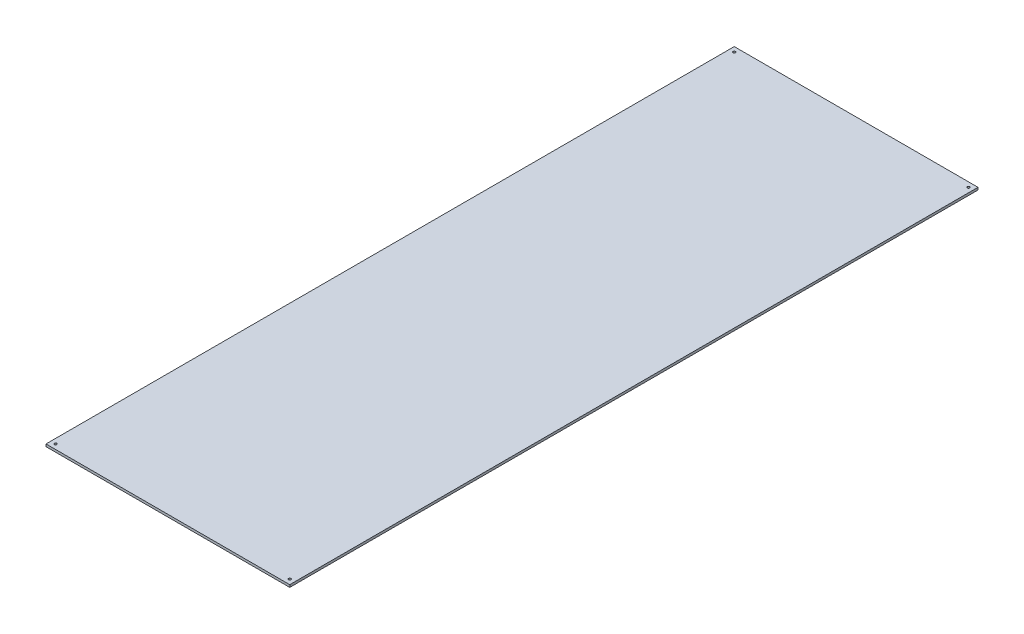
SolidWorks part; units mm, degrees
ref_plane "Front Plane" through (0, 0, 0) normal (0, 0, 1) x (1, 0, 0)
ref_plane "Top Plane" through (0, 0, 0) normal (0, 1, 0) x (1, 0, 0)
ref_plane "Right Plane" through (0, 0, 0) normal (1, 0, 0) x (0, 0, -1)
sketch "Sketch1" plane through (0, 0, 0) normal (0, 1, 0) x (1, 0, 0)
  line L1 (-323.85, -914.4) -> (323.85, -914.4)
  line L2 (-323.85, -914.4) -> (-323.85, 914.4)
  line L3 (-323.85, 914.4) -> (323.85, 914.4)
  line L4 (323.85, -914.4) -> (323.85, 914.4)
  line L5 (-323.85, -914.4) -> (323.85, 914.4) construction
  line L6 (-323.85, 914.4) -> (323.85, -914.4) construction
  point P0 (0, 0)
  dimension "D1" = 647.7
  dimension "D2" = 1828.8
extrude "Boss-Extrude1" add sketch "Sketch1" along normal blind 6.35
sketch "Sketch2" plane through (0, 6.35, 0) normal (0, 1, 0) x (1, 0, 0)
  line L0 (323.85, -914.4) -> (323.85, 914.4) construction
  line L1 (323.85, 914.4) -> (-323.85, 914.4) construction
  circle A4 centre (-311.15, -901.7) radius 2.6035 construction
  circle A5 centre (311.15, -901.7) radius 2.6035 construction
  circle A6 centre (311.15, 901.7) radius 2.6035 construction
  circle A7 centre (-311.15, 901.7) radius 2.6035 construction
  circle A8 centre (311.15, -901.7) radius 3.175
  circle A9 centre (-311.15, -901.7) radius 3.175
  circle A10 centre (311.15, 901.7) radius 3.175
  circle A11 centre (-311.15, 901.7) radius 3.175
  dimension "D1" = 5.207
  dimension "D6" = 6.35
  dimension "D7" = 6.35
  dimension "D8" = 6.35
  dimension "D9" = 6.35
  dimension "D2" = 12.7
  dimension "D3" = 635
  dimension "D4" = 12.7
  dimension "D5" = 1816.1
extrude "Cut-Extrude1" cut sketch "Sketch2" against normal through all
